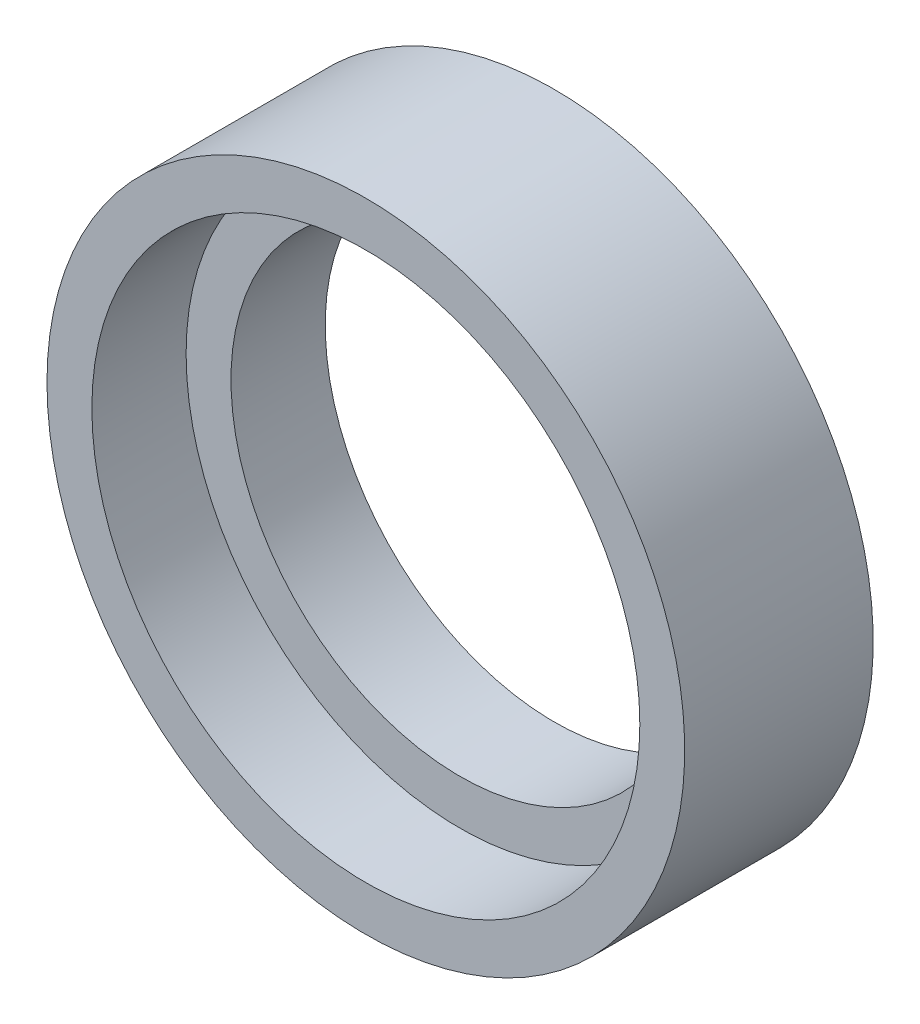
SolidWorks part; units mm, degrees
ref_plane "Front Plane" through (0, 0, 0) normal (0, 0, 1) x (1, 0, 0)
ref_plane "Top Plane" through (0, 0, 0) normal (0, 1, 0) x (1, 0, 0)
ref_plane "Right Plane" through (0, 0, 0) normal (1, 0, 0) x (0, 0, -1)
sketch "Sketch1" plane through (0, 0, 0) normal (0, 0, 1) x (1, 0, 0)
  circle A0 centre (0, 0) radius 61.05
  circle A1 centre (0, 0) radius 71.05
  dimension "D1" = 122.1
  dimension "D2" = 10
extrude "Boss-Extrude1" add sketch "Sketch1" along normal blind 21
sketch "Sketch2" plane through (0, 0, 0) normal (0, 0, -1) x (-1, 0, 0)
  circle A0 centre (0, 0) radius 51.05
  circle A1 centre (0, 0) radius 71.05
  dimension "D1" = 102.1
extrude "Boss-Extrude2" add sketch "Sketch2" along normal blind 21
